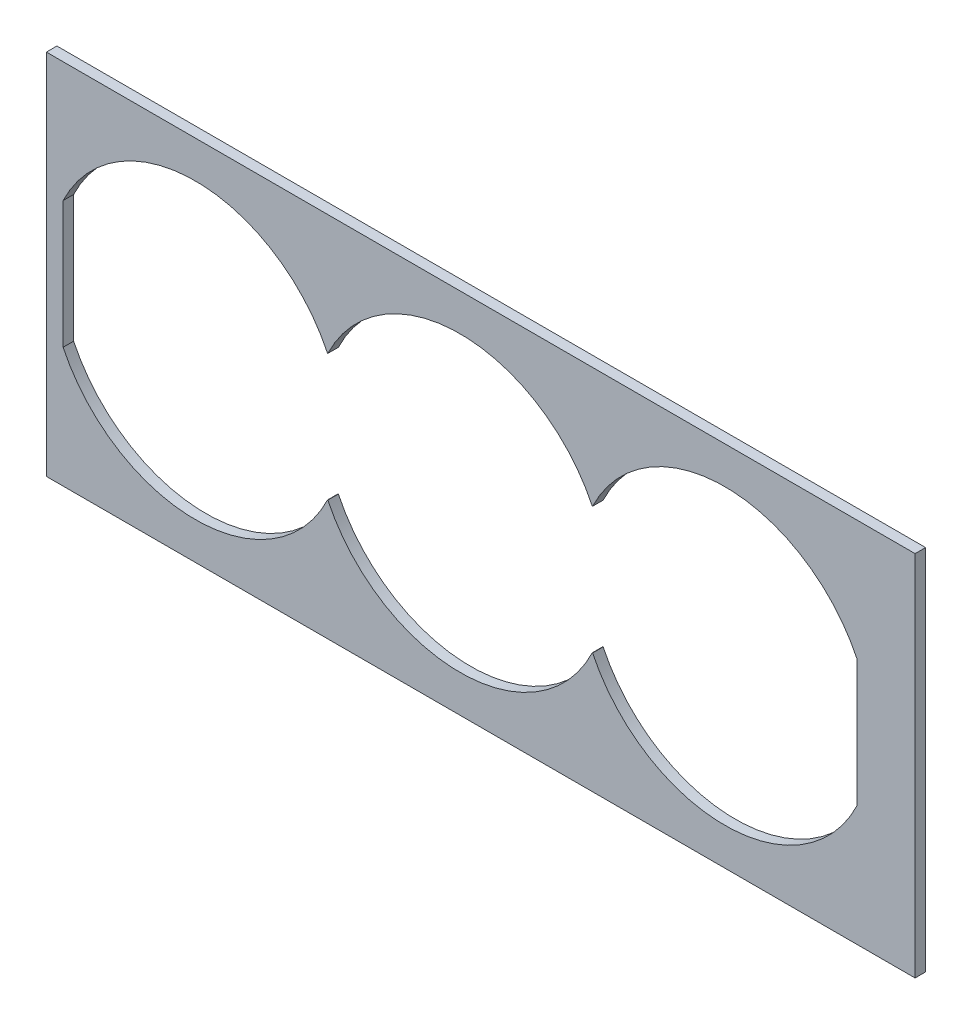
SolidWorks part; units mm, degrees
ref_plane "Front" through (0, 0, 0) normal (0, 0, 1) x (1, 0, 0)
ref_plane "Top" through (0, 0, 0) normal (0, 1, 0) x (1, 0, 0)
ref_plane "Right" through (0, 0, 0) normal (1, 0, 0) x (0, 0, -1)
sketch "Sketch4" plane through (0, 0, 0) normal (0, 0, 1) x (1, 0, 0)
  line L0 (165.1, 0) -> (165.1, 139.7) construction
  line L1 (207.493, 93.9963) -> (207.493, 45.7037) construction
  line L2 (0, 0) -> (330.2, 0)
  line L3 (165.1, 69.85) -> (56.604, 69.85) construction
  line L4 (6.35, 93.9963) -> (6.35, 45.7037)
  line L5 (106.858, 93.9963) -> (106.858, 45.7037) construction
  line L6 (0, 0) -> (0, 139.7)
  line L7 (0, 139.7) -> (330.2, 139.7)
  line L8 (330.2, 0) -> (330.2, 139.7)
  line L9 (106.985, 93.9963) -> (106.985, 45.7037) construction
  line L10 (308.128, 93.9963) -> (308.128, 45.7037)
  line L11 (207.62, 93.9963) -> (207.62, 45.7037) construction
  line L12 (106.858, 93.9963) -> (106.985, 93.9963)
  line L13 (207.493, 93.9963) -> (207.62, 93.9963)
  line L14 (207.62, 45.7037) -> (207.493, 45.7037)
  line L15 (106.985, 45.7037) -> (106.858, 45.7037)
  arc A0 (6.35, 45.7037) -> (106.858, 45.7037) centre (56.604, 69.85) ccw
  arc A1 (106.858, 93.9963) -> (6.35, 93.9963) centre (56.604, 69.85) ccw
  arc A2 (106.985, 45.7037) -> (207.493, 45.7037) centre (157.239, 69.85) ccw
  arc A3 (207.493, 93.9963) -> (106.985, 93.9963) centre (157.239, 69.85) ccw
  arc A4 (207.62, 45.7037) -> (308.128, 45.7037) centre (257.874, 69.85) ccw
  arc A5 (308.128, 93.9963) -> (207.62, 93.9963) centre (257.874, 69.85) ccw
  point P8 (165.1, 69.85)
  dimension "D2" = 111.508
  dimension "D1" = 100.508
  dimension "D3" = 139.7
  dimension "D4" = 330.2
  dimension "D6" = 6.35
  dimension "D7" = 0.127
  dimension "D5" = 3
extrude "Boss-Extrude3" add sketch "Sketch4" along normal blind 4
